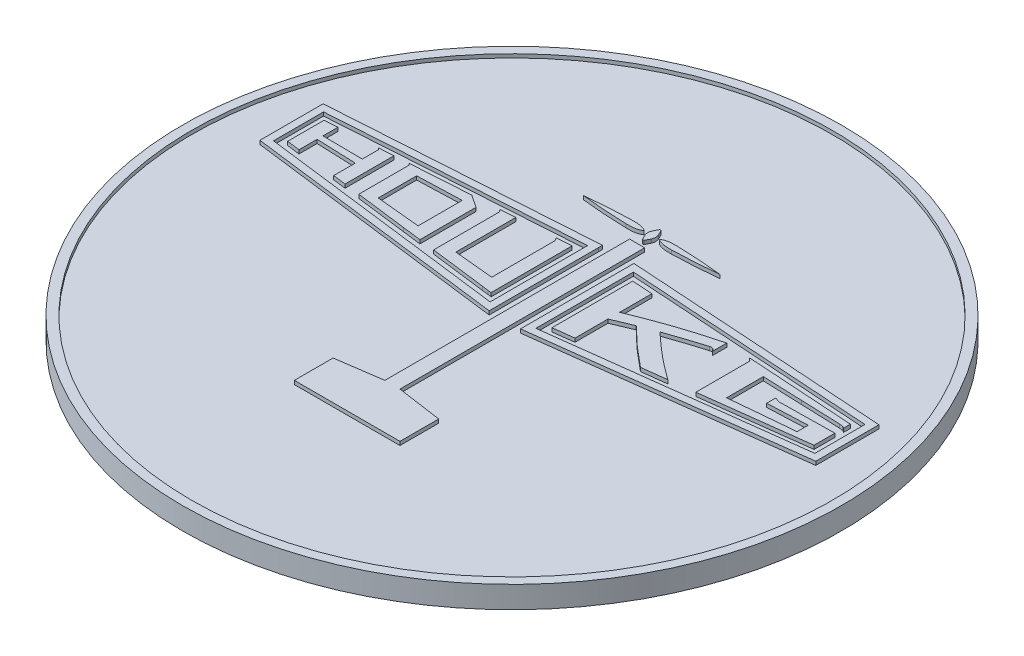
SolidWorks part; units mm, degrees
ref_plane "前视基准面" through (0, 0, 0) normal (0, 0, 1) x (1, 0, 0)
ref_plane "上视基准面" through (0, 0, 0) normal (0, 1, 0) x (1, 0, 0)
ref_plane "右视基准面" through (0, 0, 0) normal (1, 0, 0) x (0, 0, -1)
other "Configuration Table"
sketch "草图3" plane through (0, 0, 0) normal (0, 1, 0) x (1, 0, 0)
  line L71 (-0.0763, 27.6661) -> (-0.3104, 27.1979)
  line L72 (-0.3104, 26.3717) -> (-0.0763, 25.9035)
  line L73 (0.144, 25.9035) -> (0.3781, 26.3717)
  line L74 (0.3781, 27.1979) -> (0.144, 27.6661)
  line L75 (-1.6818, 22.7001) -> (-1.6766, 10.7341)
  line L76 (-1.6766, 10.7341) -> (-30.3273, 14.3434)
  line L77 (-30.3273, 14.3434) -> (-30.3273, 21.2459)
  line L78 (-1.6819, 23.1215) -> (-1.6818, 22.7001)
  line L79 (-2.4649, 11.6272) -> (-2.4695, 22.2788)
  line L80 (-2.4695, 22.2788) -> (-29.5362, 20.5065)
  line L81 (-29.5362, 20.5065) -> (-29.5362, 15.0375)
  line L82 (-29.5362, 15.0375) -> (-2.4649, 11.6272)
  line L83 (-3.2896, 21.4035) -> (-4.9045, 21.2978)
  line L84 (-9.0496, 17.7532) -> (-9.0496, 21.0264)
  line L85 (-9.0496, 21.0264) -> (-10.6526, 20.9214)
  line L86 (-10.469, 17.0396) -> (-10.469, 13.4627)
  line L87 (-10.469, 13.4627) -> (-4.3771, 12.6953)
  line L88 (-3.6601, 12.605) -> (-3.2896, 12.5583)
  line L89 (-3.2896, 12.5583) -> (-3.2896, 16.7993)
  line L90 (-13.568, 20.7305) -> (-19.9989, 20.3094)
  line L91 (-19.8263, 17.3664) -> (-19.8263, 14.6415)
  line L92 (-19.8263, 14.6415) -> (-14.2473, 13.9387)
  line L93 (-21.5404, 20.2085) -> (-23.1222, 20.1049)
  line L94 (-27.2977, 19.043) -> (-27.2977, 19.8315)
  line L95 (-27.2977, 19.8315) -> (-28.7172, 19.7386)
  line L96 (-28.7172, 19.7386) -> (-28.7172, 15.7616)
  line L97 (-28.7172, 15.7616) -> (-27.2977, 15.5827)
  line L98 (-27.2977, 15.5827) -> (-27.2977, 16.5581)
  line L99 (-22.9598, 16.2055) -> (-22.9598, 15.0362)
  line L100 (-22.9598, 15.0362) -> (-21.5404, 14.8575)
  line L101 (-21.5404, 14.8575) -> (-21.5404, 17.5433)
  line L102 (-21.5404, 17.5433) -> (-21.5404, 20.2085)
  line L103 (-0.7924, -2.0831) -> (0.86, -2.0831)
  line L104 (0.86, -2.0831) -> (0.86, 25.1888)
  line L105 (0.86, 25.1888) -> (-0.7924, 25.1888)
  line L106 (-0.7924, 25.1888) -> (-0.7924, -2.0831)
  line L107 (-0.4139, -1.4909) -> (-5.7336, -2.2563)
  line L108 (-5.7336, -2.2563) -> (-5.7337, -6.4866)
  line L109 (-5.7337, -6.4866) -> (0.0338, -6.4866)
  line L110 (0.0338, -6.4866) -> (5.8014, -6.4866)
  line L111 (5.8014, -6.4866) -> (5.8014, -2.2563)
  line L112 (5.8014, -2.2563) -> (0.4815, -1.4909)
  line L113 (0.4815, -1.4909) -> (0.0338, -0.9514)
  line L114 (0.0338, -0.9514) -> (-0.4139, -1.4909)
  line L115 (23.8837, 20.0595) -> (28.7849, 19.7386)
  line L116 (28.7849, 19.7386) -> (28.7849, 18.9631)
  line L117 (28.7849, 18.042) -> (28.7849, 15.7616)
  line L118 (28.7849, 15.7616) -> (17.3166, 14.3168)
  line L119 (17.3166, 14.3168) -> (17.3166, 15.7914)
  line L120 (22.8855, 20.124) -> (23.8837, 20.0595)
  line L121 (3.3561, 18.6447) -> (3.3573, 21.3841)
  line L122 (3.3561, 16.7809) -> (3.3561, 18.6447)
  line L123 (2.5371, 22.2788) -> (2.5325, 11.6272)
  line L124 (2.5325, 11.6272) -> (29.6039, 15.0375)
  line L125 (29.6039, 15.0375) -> (29.6039, 20.5065)
  line L126 (29.6039, 20.5065) -> (2.5371, 22.2788)
  line L127 (1.7444, 11.1807) -> (1.7496, 23.1215)
  line L128 (30.3949, 21.2459) -> (30.3949, 14.3434)
  line L129 (1.7442, 10.7341) -> (1.7444, 11.1807)
  circle A0 centre (0, 11.5538) radius 35
  circle A1 centre (0, 11.5538) radius 36
  spline S87 degree 3 poles (-7.4019, 26.7849) (-5.7974, 26.9404) (-4.1928, 27.096) (-2.4447, 27.1153) knots 0 0 0 0 0.2 0.2 0.2 0.2
  spline S88 degree 3 poles (-2.4447, 27.1153) (-1.8518, 27.1219) (-1.2423, 27.1128) (-0.7924, 26.7849) knots 0.2 0.2 0.2 0.2 0.4 0.4 0.4 0.4
  spline S89 degree 3 poles (-0.7924, 26.7849) (-1.2423, 26.4569) (-1.8518, 26.4478) (-2.4447, 26.4543) knots 0.4 0.4 0.4 0.4 0.6 0.6 0.6 0.6
  spline S90 degree 3 poles (-2.4447, 26.4543) (-4.1928, 26.4737) (-5.7974, 26.6292) (-7.4019, 26.7849) knots 0.6 0.6 0.6 0.6 1 1 1 1
  spline S91 degree 3 poles (-0.3104, 27.1979) (-0.4335, 26.9516) (-0.4335, 26.6181) (-0.3104, 26.3717) knots 0.090909 0.090909 0.090909 0.090909 0.181818 0.181818 0.181818 0.181818
  spline S92 degree 3 poles (-0.0763, 25.9035) (-0.0554, 25.8619) (-0.0128, 25.8355) (0.0338, 25.8355) knots 0.272727 0.272727 0.272727 0.272727 0.363636 0.363636 0.363636 0.363636
  spline S93 degree 3 poles (0.0338, 25.8355) (0.0805, 25.8355) (0.1231, 25.8619) (0.144, 25.9035) knots 0.363636 0.363636 0.363636 0.363636 0.454545 0.454545 0.454545 0.454545
  spline S94 degree 3 poles (0.3781, 26.3717) (0.5013, 26.6181) (0.5013, 26.9516) (0.3781, 27.1979) knots 0.545455 0.545455 0.545455 0.545455 0.636364 0.636364 0.636364 0.636364
  spline S95 degree 3 poles (0.144, 27.6661) (0.1231, 27.7078) (0.0805, 27.7342) (0.0338, 27.7342) knots 0.727273 0.727273 0.727273 0.727273 0.818182 0.818182 0.818182 0.818182
  spline S96 degree 3 poles (0.0338, 27.7342) (-0.0128, 27.7342) (-0.0554, 27.7078) (-0.0763, 27.6661) knots 0.818182 0.818182 0.818182 0.818182 1 1 1 1
  spline S97 degree 3 poles (7.4696, 26.7849) (5.8651, 26.9404) (4.2606, 27.096) (2.5125, 27.1153) knots 0 0 0 0 0.2 0.2 0.2 0.2
  spline S98 degree 3 poles (2.5125, 27.1153) (1.9195, 27.1219) (1.3101, 27.1128) (0.8601, 26.7849) knots 0.2 0.2 0.2 0.2 0.4 0.4 0.4 0.4
  spline S99 degree 3 poles (0.8601, 26.7849) (1.3101, 26.4569) (1.9195, 26.4478) (2.5125, 26.4543) knots 0.4 0.4 0.4 0.4 0.6 0.6 0.6 0.6
  spline S100 degree 3 poles (2.5125, 26.4543) (4.2606, 26.4737) (5.8651, 26.6292) (7.4696, 26.7849) knots 0.6 0.6 0.6 0.6 1 1 1 1
  spline S101 degree 3 poles (-30.3273, 21.2459) (-20.7787, 21.8709) (-11.2303, 22.4961) (-1.6819, 23.1215) knots 0.5 0.5 0.5 0.5 0.666667 0.666667 0.666667 0.666667
  spline S102 degree 3 poles (-4.9045, 21.2978) (-4.841, 21.1793) (-4.7776, 21.0608) (-4.7116, 20.9432) knots 0.055556 0.055556 0.055556 0.055556 0.111111 0.111111 0.111111 0.111111
  spline S103 degree 3 poles (-4.7116, 20.9432) (-4.7116, 19.7942) (-4.7116, 18.6453) (-4.7116, 17.4972) knots 0.111111 0.111111 0.111111 0.111111 0.166667 0.166667 0.166667 0.166667
  spline S104 degree 3 poles (-4.7116, 17.4972) (-4.7116, 16.3482) (-4.7116, 15.2002) (-4.7116, 14.0521) knots 0.166667 0.166667 0.166667 0.166667 0.222222 0.222222 0.222222 0.222222
  spline S105 degree 3 poles (-4.7116, 14.0521) (-6.1593, 14.1911) (-7.6044, 14.3292) (-9.0496, 14.4673) knots 0.222222 0.222222 0.222222 0.222222 0.277778 0.277778 0.277778 0.277778
  spline S106 degree 3 poles (-9.0496, 14.4673) (-9.0496, 15.5629) (-9.0496, 16.6584) (-9.0496, 17.7532) knots 0.277778 0.277778 0.277778 0.277778 0.333333 0.333333 0.333333 0.333333
  spline S107 degree 3 poles (-10.6526, 20.9214) (-10.5923, 20.8226) (-10.5318, 20.7254) (-10.469, 20.6265) knots 0.444444 0.444444 0.444444 0.444444 0.5 0.5 0.5 0.5
  spline S108 degree 3 poles (-10.469, 20.6265) (-10.469, 19.4306) (-10.469, 18.2346) (-10.469, 17.0396) knots 0.5 0.5 0.5 0.5 0.555556 0.555556 0.555556 0.555556
  spline S109 degree 3 poles (-4.3771, 12.6953) (-4.1453, 12.6665) (-3.9134, 12.6375) (-3.6816, 12.6085) knots 0.666667 0.666667 0.666667 0.666667 0.722222 0.722222 0.722222 0.722222
  spline S110 degree 3 poles (-3.6816, 12.6085) (-3.6744, 12.6076) (-3.6673, 12.6064) (-3.6601, 12.605) knots 0.722222 0.722222 0.722222 0.722222 0.777778 0.777778 0.777778 0.777778
  spline S111 degree 3 poles (-3.2896, 16.7993) (-3.2896, 18.3332) (-3.2896, 19.8688) (-3.2896, 21.4035) knots 0.888889 0.888889 0.888889 0.888889 1 1 1 1
  spline S112 degree 3 poles (-19.9989, 20.3094) (-19.9422, 20.2401) (-19.8852, 20.17) (-19.8263, 20.1009) knots 0.1 0.1 0.1 0.1 0.2 0.2 0.2 0.2
  spline S113 degree 3 poles (-19.8263, 20.1009) (-19.8263, 19.1894) (-19.8263, 18.2779) (-19.8263, 17.3664) knots 0.2 0.2 0.2 0.2 0.3 0.3 0.3 0.3
  spline S114 degree 3 poles (-14.2473, 13.9387) (-13.5597, 13.853) (-12.8718, 13.7674) (-12.1831, 13.682) knots 0.5 0.5 0.5 0.5 0.6 0.6 0.6 0.6
  spline S115 degree 3 poles (-12.1831, 13.682) (-12.1831, 14.702) (-12.1831, 15.7231) (-12.1831, 16.7432) knots 0.6 0.6 0.6 0.6 0.7 0.7 0.7 0.7
  spline S116 degree 3 poles (-12.1831, 16.7432) (-12.1831, 17.7623) (-12.1831, 18.7833) (-12.1831, 19.8044) knots 0.7 0.7 0.7 0.7 0.8 0.8 0.8 0.8
  spline S117 degree 3 poles (-12.1831, 19.8044) (-12.6447, 20.1197) (-13.1063, 20.4296) (-13.568, 20.7305) knots 0.8 0.8 0.8 0.8 1 1 1 1
  spline S118 degree 3 poles (-23.1222, 20.1049) (-23.0688, 20.0467) (-23.0152, 19.9885) (-22.9598, 19.9296) knots 0.052632 0.052632 0.052632 0.052632 0.105263 0.105263 0.105263 0.105263
  spline S119 degree 3 poles (-22.9598, 19.9296) (-22.9598, 19.6349) (-22.9598, 19.3394) (-22.9598, 19.0448) knots 0.105263 0.105263 0.105263 0.105263 0.157895 0.157895 0.157895 0.157895
  spline S120 degree 3 poles (-22.9598, 19.0448) (-22.9598, 18.7502) (-22.9598, 18.4546) (-22.9598, 18.1601) knots 0.157895 0.157895 0.157895 0.157895 0.210526 0.210526 0.210526 0.210526
  spline S121 degree 3 poles (-22.9598, 18.1601) (-24.4076, 18.1739) (-25.8527, 18.1895) (-27.2977, 18.2034) knots 0.210526 0.210526 0.210526 0.210526 0.263158 0.263158 0.263158 0.263158
  spline S122 degree 3 poles (-27.2977, 18.2034) (-27.2977, 18.4832) (-27.2977, 18.7631) (-27.2977, 19.043) knots 0.263158 0.263158 0.263158 0.263158 0.315789 0.315789 0.315789 0.315789
  spline S123 degree 3 poles (-27.2977, 16.5581) (-27.2977, 16.8904) (-27.2977, 17.2238) (-27.2977, 17.5571) knots 0.578947 0.578947 0.578947 0.578947 0.631579 0.631579 0.631579 0.631579
  spline S124 degree 3 poles (-27.2977, 17.5571) (-25.8527, 17.5027) (-24.4076, 17.4465) (-22.9598, 17.3922) knots 0.631579 0.631579 0.631579 0.631579 0.684211 0.684211 0.684211 0.684211
  spline S125 degree 3 poles (-22.9598, 17.3922) (-22.9598, 16.9964) (-22.9598, 16.6005) (-22.9598, 16.2055) knots 0.684211 0.684211 0.684211 0.684211 0.736842 0.736842 0.736842 0.736842
  spline S126 degree 3 poles (-18.4068, 19.542) (-18.4068, 18.8441) (-18.4068, 18.1444) (-18.4068, 17.4465) knots 0 0 0 0 0.142857 0.142857 0.142857 0.142857
  spline S127 degree 3 poles (-18.4068, 17.4465) (-18.4068, 16.7487) (-18.4068, 16.0499) (-18.4068, 15.3511) knots 0.142857 0.142857 0.142857 0.142857 0.285714 0.285714 0.285714 0.285714
  spline S128 degree 3 poles (-18.4068, 15.3511) (-16.8029, 15.1964) (-15.1989, 15.0427) (-13.5924, 14.8871) knots 0.285714 0.285714 0.285714 0.285714 0.428571 0.428571 0.428571 0.428571
  spline S129 degree 3 poles (-13.5924, 14.8871) (-13.5924, 15.69) (-13.5924, 16.4946) (-13.5924, 17.2974) knots 0.428571 0.428571 0.428571 0.428571 0.571429 0.571429 0.571429 0.571429
  spline S130 degree 3 poles (-13.5924, 17.2974) (-13.5924, 18.1002) (-13.5924, 18.9049) (-13.5924, 19.7086) knots 0.571429 0.571429 0.571429 0.571429 0.714286 0.714286 0.714286 0.714286
  spline S131 degree 3 poles (-13.5924, 19.7086) (-15.1989, 19.6534) (-16.8029, 19.5972) (-18.4068, 19.542) knots 0.714286 0.714286 0.714286 0.714286 1 1 1 1
  spline S132 degree 3 poles (28.7849, 18.9631) (28.7366, 19.0395) (28.6476, 19.0911) (28.5153, 19.1193) knots 0.076923 0.076923 0.076923 0.076923 0.115385 0.115385 0.115385 0.115385
  spline S133 degree 3 poles (28.5153, 19.1193) (28.3857, 19.1471) (28.2688, 19.1644) (28.1645, 19.1682) knots 0.115385 0.115385 0.115385 0.115385 0.153846 0.153846 0.153846 0.153846
  spline S134 degree 3 poles (28.1645, 19.1682) (26.7227, 19.2195) (25.2833, 19.271) (23.8416, 19.3235) knots 0.153846 0.153846 0.153846 0.153846 0.192308 0.192308 0.192308 0.192308
  spline S135 degree 3 poles (23.8416, 19.3235) (22.4048, 19.3758) (20.963, 19.429) (19.5238, 19.4814) knots 0.192308 0.192308 0.192308 0.192308 0.230769 0.230769 0.230769 0.230769
  spline S136 degree 3 poles (19.5238, 19.4814) (19.5238, 18.8114) (19.5238, 18.1414) (19.5238, 17.4723) knots 0.230769 0.230769 0.230769 0.230769 0.269231 0.269231 0.269231 0.269231
  spline S137 degree 3 poles (19.5238, 17.4723) (19.5238, 16.803) (19.5238, 16.1321) (19.5238, 15.463) knots 0.269231 0.269231 0.269231 0.269231 0.307692 0.307692 0.307692 0.307692
  spline S138 degree 3 poles (19.5238, 15.463) (20.668, 15.573) (21.8198, 15.6824) (22.9618, 15.7914) knots 0.307692 0.307692 0.307692 0.307692 0.346154 0.346154 0.346154 0.346154
  spline S139 degree 3 poles (22.9618, 15.7914) (24.1085, 15.9008) (25.4309, 16.0097) (26.5777, 16.1189) knots 0.346154 0.346154 0.346154 0.346154 0.384615 0.384615 0.384615 0.384615
  spline S140 degree 3 poles (26.5777, 16.1189) (26.5777, 16.3202) (26.5777, 16.5226) (26.5777, 16.7259) knots 0.384615 0.384615 0.384615 0.384615 0.423077 0.423077 0.423077 0.423077
  spline S141 degree 3 poles (26.5777, 16.7259) (26.5777, 16.9282) (26.5777, 17.1306) (26.5777, 17.3328) knots 0.423077 0.423077 0.423077 0.423077 0.461538 0.461538 0.461538 0.461538
  spline S142 degree 3 poles (26.5777, 17.3328) (25.1816, 17.2725) (23.6178, 17.2113) (22.2268, 17.1492) knots 0.461538 0.461538 0.461538 0.461538 0.5 0.5 0.5 0.5
  spline S143 degree 3 poles (22.2268, 17.1492) (22.2268, 17.4775) (22.2268, 17.8068) (22.2268, 18.1351) knots 0.5 0.5 0.5 0.5 0.538462 0.538462 0.538462 0.538462
  spline S144 degree 3 poles (22.2268, 18.1351) (22.4023, 18.0722) (22.5803, 18.0118) (22.7583, 17.9505) knots 0.538462 0.538462 0.538462 0.538462 0.576923 0.576923 0.576923 0.576923
  spline S145 degree 3 poles (22.7583, 17.9505) (24.7087, 17.9816) (26.832, 18.0118) (28.7849, 18.042) knots 0.576923 0.576923 0.576923 0.576923 0.615385 0.615385 0.615385 0.615385
  spline S146 degree 3 poles (17.3166, 15.7914) (17.3166, 16.2822) (17.3166, 16.7746) (17.3166, 17.2672) knots 0.730769 0.730769 0.730769 0.730769 0.769231 0.769231 0.769231 0.769231
  spline S147 degree 3 poles (17.3166, 17.2672) (17.3166, 17.758) (17.3166, 18.2506) (17.3166, 18.7413) knots 0.769231 0.769231 0.769231 0.769231 0.807692 0.807692 0.807692 0.807692
  spline S148 degree 3 poles (17.3166, 18.7413) (17.3166, 19.2321) (17.3166, 19.7255) (17.3166, 20.2171) knots 0.807692 0.807692 0.807692 0.807692 0.846154 0.846154 0.846154 0.846154
  spline S149 degree 3 poles (17.3166, 20.2171) (17.2072, 20.3121) (17.0978, 20.408) (16.991, 20.5056) knots 0.846154 0.846154 0.846154 0.846154 0.884615 0.884615 0.884615 0.884615
  spline S150 degree 3 poles (16.991, 20.5056) (18.9541, 20.3778) (20.9224, 20.2509) (22.8855, 20.124) knots 0.884615 0.884615 0.884615 0.884615 0.923077 0.923077 0.923077 0.923077
  spline S151 degree 3 poles (3.3573, 21.3841) (4.0995, 21.3336) (4.8466, 21.283) (5.5938, 21.2351) knots 0.041667 0.041667 0.041667 0.041667 0.083333 0.083333 0.083333 0.083333
  spline S152 degree 3 poles (5.5938, 21.2351) (5.5938, 20.6494) (5.5938, 20.0628) (5.5938, 19.477) knots 0.083333 0.083333 0.083333 0.083333 0.125 0.125 0.125 0.125
  spline S153 degree 3 poles (5.5938, 19.477) (5.5938, 18.8921) (5.5938, 18.3074) (5.5938, 17.7207) knots 0.125 0.125 0.125 0.125 0.166667 0.166667 0.166667 0.166667
  spline S154 degree 3 poles (5.5938, 17.7207) (7.0534, 18.3091) (8.4947, 18.87) (9.9727, 19.367) knots 0.166667 0.166667 0.166667 0.166667 0.208333 0.208333 0.208333 0.208333
  spline S155 degree 3 poles (9.9727, 19.367) (11.4139, 19.8516) (12.8945, 20.2695) (14.3567, 20.6617) knots 0.208333 0.208333 0.208333 0.208333 0.25 0.25 0.25 0.25
  spline S156 degree 3 poles (14.3567, 20.6617) (14.3567, 20.1319) (14.3567, 19.604) (14.3567, 19.0741) knots 0.25 0.25 0.25 0.25 0.291667 0.291667 0.291667 0.291667
  spline S157 degree 3 poles (14.3567, 19.0741) (14.2981, 19.2019) (14.225, 19.2968) (14.1354, 19.3572) knots 0.291667 0.291667 0.291667 0.291667 0.333333 0.333333 0.333333 0.333333
  spline S158 degree 3 poles (14.1354, 19.3572) (14.0419, 19.4202) (13.8987, 19.4439) (13.7413, 19.3981) knots 0.333333 0.333333 0.333333 0.333333 0.375 0.375 0.375 0.375
  spline S159 degree 3 poles (13.7413, 19.3981) (12.3628, 18.9966) (11.0127, 18.5398) (9.6523, 18.0615) knots 0.375 0.375 0.375 0.375 0.416667 0.416667 0.416667 0.416667
  spline S160 degree 3 poles (9.6523, 18.0615) (10.0617, 17.6807) (10.4711, 17.3054) (10.8805, 16.9406) knots 0.416667 0.416667 0.416667 0.416667 0.458333 0.458333 0.458333 0.458333
  spline S161 degree 3 poles (10.8805, 16.9406) (11.2899, 16.5758) (11.7013, 16.2193) (12.1214, 15.8729) knots 0.458333 0.458333 0.458333 0.458333 0.5 0.5 0.5 0.5
  spline S162 degree 3 poles (12.1214, 15.8729) (12.932, 15.2049) (13.7692, 14.5755) (14.5957, 13.9774) knots 0.5 0.5 0.5 0.5 0.541667 0.541667 0.541667 0.541667
  spline S163 degree 3 poles (14.5957, 13.9774) (13.7108, 13.8655) (12.8284, 13.7546) (11.9435, 13.6437) knots 0.541667 0.541667 0.541667 0.541667 0.583333 0.583333 0.583333 0.583333
  spline S164 degree 3 poles (11.9435, 13.6437) (11.2467, 14.2046) (10.5393, 14.7826) (9.8532, 15.3928) knots 0.583333 0.583333 0.583333 0.583333 0.625 0.625 0.625 0.625
  spline S165 degree 3 poles (9.8532, 15.3928) (9.1483, 16.0197) (8.4622, 16.6762) (7.768, 17.356) knots 0.625 0.625 0.625 0.625 0.666667 0.666667 0.666667 0.666667
  spline S166 degree 3 poles (7.768, 17.356) (7.0433, 17.0622) (6.3186, 16.7596) (5.5938, 16.4472) knots 0.666667 0.666667 0.666667 0.666667 0.708333 0.708333 0.708333 0.708333
  spline S167 degree 3 poles (5.5938, 16.4472) (5.5938, 15.8464) (5.5938, 15.2437) (5.5938, 14.6448) knots 0.708333 0.708333 0.708333 0.708333 0.75 0.75 0.75 0.75
  spline S168 degree 3 poles (5.5938, 14.6448) (5.5938, 14.044) (5.5938, 13.4413) (5.5938, 12.8422) knots 0.75 0.75 0.75 0.75 0.791667 0.791667 0.791667 0.791667
  spline S169 degree 3 poles (5.5938, 12.8422) (4.8462, 12.7482) (4.0986, 12.6532) (3.3561, 12.5609) knots 0.791667 0.791667 0.791667 0.791667 0.833333 0.833333 0.833333 0.833333
  spline S170 degree 3 poles (3.3561, 12.5609) (3.3561, 13.2638) (3.3561, 13.9667) (3.3561, 14.6705) knots 0.833333 0.833333 0.833333 0.833333 0.875 0.875 0.875 0.875
  spline S171 degree 3 poles (3.3561, 14.6705) (3.3561, 15.3734) (3.3561, 16.0763) (3.3561, 16.7809) knots 0.875 0.875 0.875 0.875 0.916667 0.916667 0.916667 0.916667
  spline S172 degree 3 poles (1.7496, 23.1215) (11.298, 22.4961) (20.8465, 21.8709) (30.3949, 21.2459) knots 0.166667 0.166667 0.166667 0.166667 0.333333 0.333333 0.333333 0.333333
  spline S173 degree 3 poles (30.3949, 14.3434) (20.8447, 13.1402) (11.2945, 11.9371) (1.7442, 10.7341) knots 0.5 0.5 0.5 0.5 0.666667 0.666667 0.666667 0.666667
  dimension "D3" = 70
  dimension "D4" = 72
  dimension "D1" = 0.86
  dimension "D2" = 13.635
extrude "凸台-拉伸2" add sketch "草图3" along normal blind 0.4 contours A1 A0 | L111 L112 L104 L103 L106 L107 L108 L109 L110 | L113 L114 L107 L106 L103 L104 L112 | L114 L113 L112 L104 L105 L106 L107 | S90 S89 S88 S87 | S101 L77 L76 L75 L78 L82 L81 L80 L79 | S173 L128 S172 L127 L129 L126 L125 L124 L123 | L89 S111 L83 S102 S103 S104 S105 S106 L84 L85 S107 S108 L86 L87 S109 S110 L88 | S116 S117 L90 S112 S113 L91 L92 S114 S115 S131 S130 S129 S128 S127 S126 | S124 S125 L99 L100 L101 L102 L93 S118 S119 S120 S121 S122 L94 L95 L96 L97 L98 S123 | S171 S170 S169 S168 S167 S166 S165 S164 S163 S162 S161 S160 S159 S158 S157 S156 S155 S154 S153 S152 S151 L121 L122 | S150 S149 S148 S147 S146 L119 L118 L117 S145 S144 S143 S142 S141 S140 S139 S138 S137 S136 S135 S134 S133 S132 L116 L115 L120 | L71 S91 L72 S92 S93 L73 S94 L74 S95 S96 | S98 S99 S100 S97
sketch "草图9" plane through (0, 0, 0) normal (0, -1, 0) x (1, 0, 0)
  circle A0 centre (0, -11.5538) radius 36 construction
  circle A1 centre (0, -11.5538) radius 36
sketch "草图10" plane through (0, 0, 0) normal (0, -1, 0) x (1, 0, 0)
  circle A1 centre (0, -11.5538) radius 36
extrude "凸台-拉伸3" add sketch "草图10" along normal blind 2
